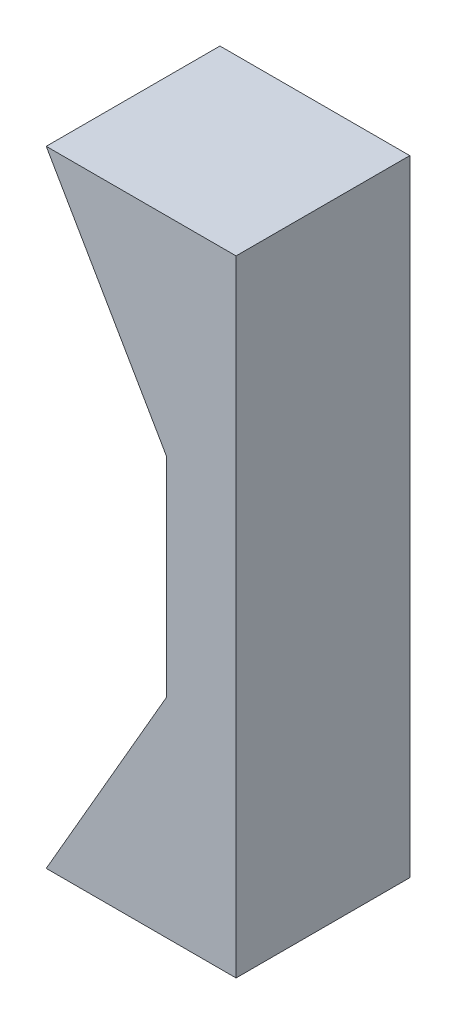
SolidWorks part; units mm, degrees
ref_plane "Front Plane" through (0, 0, 0) normal (0, 0, 1) x (1, 0, 0)
ref_plane "Top Plane" through (0, 0, 0) normal (0, 1, 0) x (1, 0, 0)
ref_plane "Right Plane" through (0, 0, 0) normal (1, 0, 0) x (0, 0, -1)
sketch "Sketch1" plane through (0, 0, 0) normal (0, 0, 1) x (1, 0, 0)
  line L0 (0, 30) -> (0, -30)
  line L1 (0, 30) -> (-34.641, 90)
  line L2 (-34.641, 90) -> (0, 90)
  line L3 (20, 90) -> (20, -90)
  line L4 (0, 30) -> (0, 90) construction
  line L5 (0, 0) -> (20, 0) construction
  line L9 (0, -30) -> (0, -90) construction
  line L11 (-34.641, -90) -> (0, -90)
  line L12 (0, -30) -> (-34.641, -90)
  line L13 (0, 90) -> (20, 90)
  line L14 (20, -90) -> (0, -90)
  point P4 (0, 0)
  point P11 (0, 0)
  dimension "D1" = 30
  dimension "D2" = 60
  dimension "D3" = 150
  dimension "D4" = 20
extrude "Boss-Extrude1" add sketch "Sketch1" along normal blind 50
